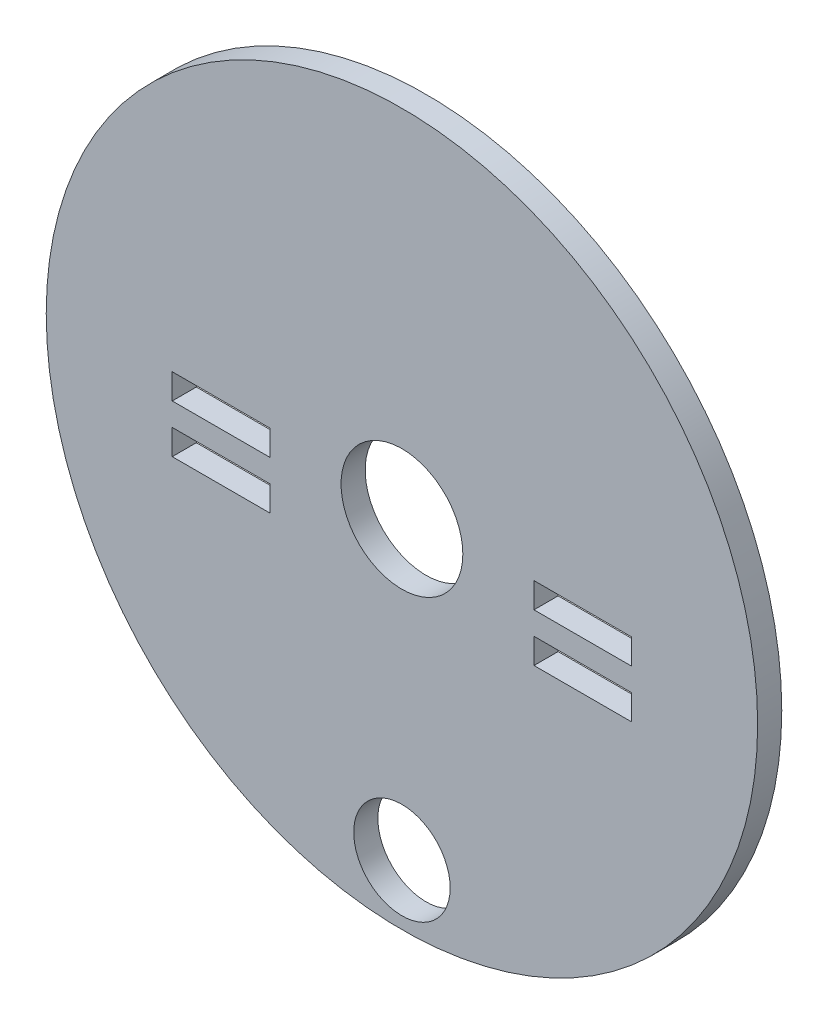
SolidWorks part; units mm, degrees
ref_plane "前视基准面" through (0, 0, 0) normal (0, 0, 1) x (1, 0, 0)
ref_plane "上视基准面" through (0, 0, 0) normal (0, 1, 0) x (1, 0, 0)
ref_plane "右视基准面" through (0, 0, 0) normal (1, 0, 0) x (0, 0, -1)
sketch "草图1" plane through (0, 0, 0) normal (0, 0, 1) x (1, 0, 0)
  line L0 (0, 0) -> (0, 4) construction
  line L1 (0, 4) -> (-15, 4) construction
  line L2 (0, 2) -> (-3.9018, 2) construction
  line L3 (-19.05, 5.05) -> (-10.95, 5.05)
  line L4 (-19.05, 5.05) -> (-19.05, 2.95)
  line L5 (-19.05, 2.95) -> (-10.95, 2.95)
  line L6 (-10.95, 5.05) -> (-10.95, 2.95)
  line L7 (-19.05, 5.05) -> (-10.95, 2.95) construction
  line L8 (-19.05, 2.95) -> (-10.95, 5.05) construction
  line L9 (-10.95, -1.05) -> (-10.95, 1.05)
  line L10 (-19.05, -1.05) -> (-10.95, -1.05)
  line L11 (-19.05, -1.05) -> (-19.05, 1.05)
  line L12 (-19.05, 1.05) -> (-10.95, 1.05)
  line L13 (10.95, 5.05) -> (10.95, 2.95)
  line L14 (19.05, 5.05) -> (10.95, 5.05)
  line L15 (19.05, 5.05) -> (19.05, 2.95)
  line L16 (19.05, 2.95) -> (10.95, 2.95)
  line L17 (19.05, 1.05) -> (10.95, 1.05)
  line L18 (19.05, -1.05) -> (19.05, 1.05)
  line L19 (19.05, -1.05) -> (10.95, -1.05)
  line L20 (10.95, -1.05) -> (10.95, 1.05)
  line L21 (0, 4) -> (0, -20.5) construction
  circle A0 centre (0, 0) radius 2.05 construction
  circle A1 centre (0, 4) radius 2.05 construction
  circle A2 centre (0, 4) radius 5.05
  circle A4 centre (0, 4) radius 12 construction
  circle A6 centre (0, 4) radius 29.5
  circle A9 centre (0, -8.5) radius 2.05 construction
  circle A10 centre (0, -25.5) radius 2.7066 construction
  circle A13 centre (0, -20.5) radius 4
  dimension "D1" = 4.1
  dimension "D3" = 4.1
  dimension "D7" = 10.1
  dimension "D9" = 24
  dimension "D10" = 59
  dimension "D11" = 8.5
  dimension "D2" = 4
  dimension "D4" = 15
  dimension "D5" = 8.1
  dimension "D6" = 2.1
  dimension "D8" = 0
extrude "凸台-拉伸1" add sketch "草图1" along normal blind 2
